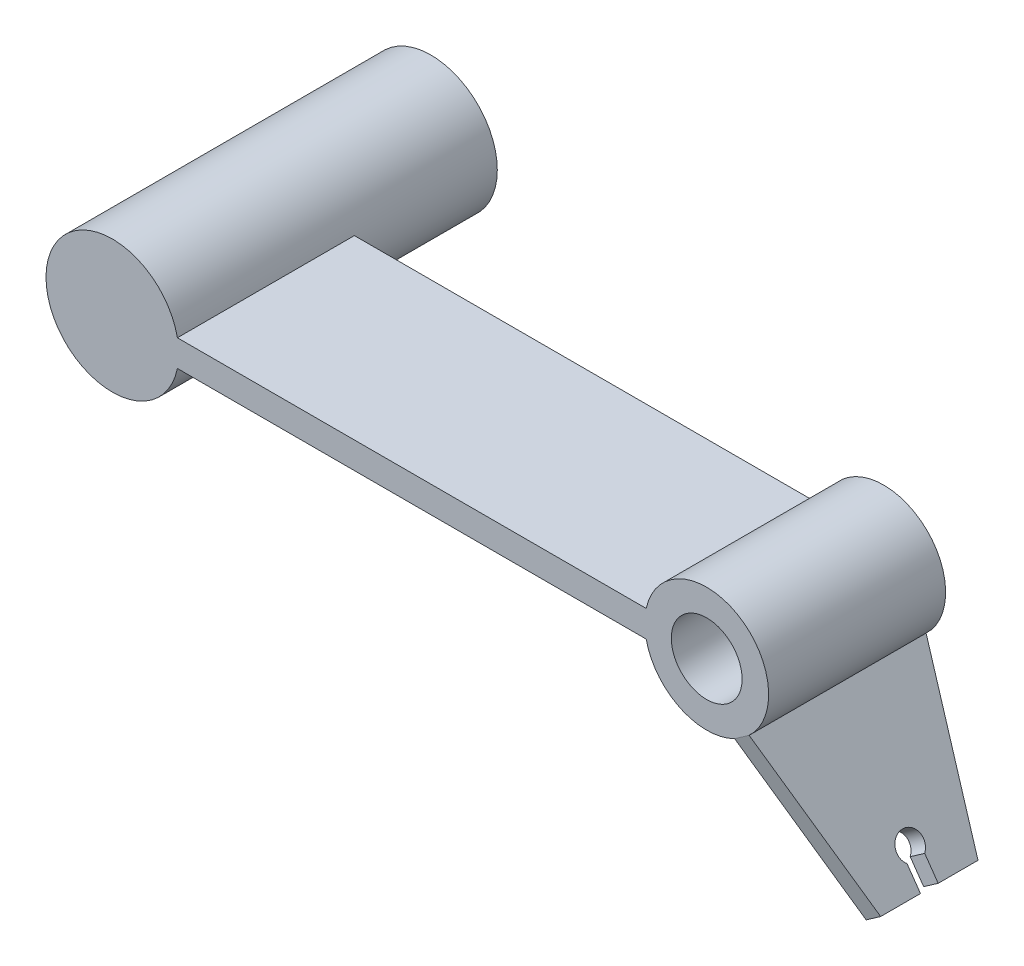
SolidWorks part; units mm, degrees
ref_plane "Front Plane" through (0, 0, 0) normal (0, 0, 1) x (1, 0, 0)
ref_plane "Top Plane" through (0, 0, 0) normal (0, 1, 0) x (1, 0, 0)
ref_plane "Right Plane" through (0, 0, 0) normal (1, 0, 0) x (0, 0, -1)
sketch "Sketch2" plane through (0, 0, 0) normal (0, 0, 1) x (1, 0, 0)
  line L0 (0, 0) -> (-7, 0) construction
  line L1 (-7, 0) -> (-37, 0) construction
  line L3 (-67.1626, 1.5) -> (-6.8374, 1.5)
  line L4 (-67.1626, 1.5) -> (-67.1626, -1.5)
  line L5 (-67.1626, -1.5) -> (-6.8374, -1.5)
  line L7 (-67.1626, 1.5) -> (-6.8374, -1.5) construction
  line L8 (-67.1626, -1.5) -> (-6.8374, 1.5) construction
  circle A0 centre (0, 0) radius 4
  arc A1 (-6.8374, -1.5) -> (-6.8374, 1.5) centre (0, 0) ccw
  dimension "D1" = 8
  dimension "D2" = 3
  dimension "D3" = 3
  dimension "D4" = 30
  dimension "D5" = 7
extrude "Boss-Extrude1" add sketch "Sketch2" along normal blind 20
sketch "Sketch3" plane through (0, 0, 20) normal (0, 0, 1) x (1, 0, 0)
  line L0 (-67.1626, 1.5) -> (-67.1626, -1.5) construction
  circle A0 centre (-67.1626, 0) radius 7.5
  dimension "D1" = 15
extrude "Boss-Extrude2" add sketch "Sketch3" against normal blind 36
sketch "Sketch4" plane through (0, 0, 20) normal (0, 0, 1) x (1, 0, 0)
  line L0 (0, 0) -> (14.3394, -20.4788) construction
  line L2 (-59.8141, -1.5) -> (-6.8374, -1.5) construction
  line L3 (15.1586, -19.9052) -> (13.5203, -21.0524)
  line L4 (13.5203, -21.0524) -> (3.1547, -6.2488)
  line L5 (15.1586, -19.9052) -> (4.793, -5.1017)
  arc A0 (3.1547, -6.2488) -> (4.793, -5.1017) centre (0, 0) ccw
  arc A1 (-6.8374, -1.5) -> (-6.8374, 1.5) centre (0, 0) ccw construction
  dimension "D1" = 55
  dimension "D2" = 2
  dimension "D3" = 25
extrude "Boss-Extrude3" add sketch "Sketch4" against normal up to surface (20 mm away) up to face at (-29.8285, 0, 0)
sketch "Sketch5" plane through (0.8192, 0.5736, 0) normal (0.8192, 0.5736, 0) x (0, 0, -1)
  line L0 (-10, -6.9282) -> (-10, -21.2282) construction
  line L1 (0, -6.9282) -> (-20, -6.9282) construction
  line L2 (-11, -22.3462) -> (-11, -25)
  line L3 (0, -25) -> (-20, -25) construction
  line L4 (-9, -22.3462) -> (-9, -25)
  line L5 (-11, -25) -> (-9, -25)
  arc A0 (-9, -22.3462) -> (-11, -22.3462) centre (-10, -21.2282) ccw
  dimension "D1" = 2
  dimension "D2" = 3
  dimension "D3" = 1
  dimension "D4" = 14.3
extrude "Cut-Extrude1" cut sketch "Sketch5" against normal up to surface (2 mm away) contours A0 L2 L5 L4 up to face at (8.3375, -13.6506, 10)
sketch "Sketch6" plane through (0.8192, 0.5736, 0) normal (0.8192, 0.5736, 0) x (0, 0, -1)
  line L0 (-20, -6.9282) -> (-15.5, -25)
  line L1 (-11, -25) -> (-20, -25) construction
  line L2 (-15.5, -25) -> (-21.3798, -25)
  line L3 (-21.3798, -25) -> (-21.3798, -6.6211)
  line L4 (-21.3798, -6.6211) -> (-20, -6.9282)
  line L5 (0, -6.9282) -> (1.4141, -6.9282)
  line L6 (1.4141, -6.9282) -> (1.4141, -25)
  line L7 (1.4141, -25) -> (-4.5, -25)
  line L8 (0, -25) -> (-9, -25) construction
  line L9 (-4.5, -25) -> (0, -6.9282)
extrude "Cut-Extrude2" cut sketch "Sketch6" against normal up to next
sketch "Sketch7" plane through (0, 0, 9) normal (0, 0, 1) x (1, 0, 0)
  line L0 (-25.2484, -1.5) -> (8.3375, -13.6506)
  line L1 (-59.8141, -1.5) -> (-6.8374, -1.5) construction
  line L2 (13.5203, -21.0524) -> (3.1547, -6.2488) construction
  line L3 (8.3375, -13.6506) -> (3.1547, -6.2488)
  line L4 (3.1547, -6.2488) -> (-6.8374, -1.5)
  line L5 (-6.8374, -1.5) -> (-25.2484, -1.5)
  line L6 (0, 0) -> (-3.402, -9.4035) construction
  dimension "D1" = 10
extrude "Boss-Extrude4" add sketch "Sketch7" along normal blind 2
